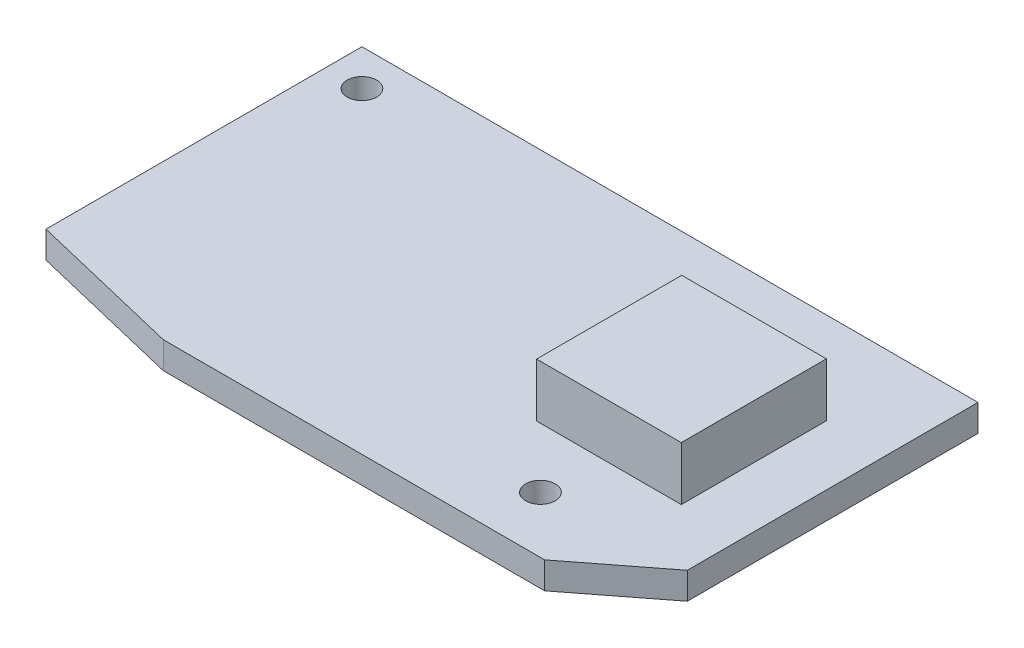
SolidWorks part; units mm, degrees
ref_plane "前视基准面" through (0, 0, 0) normal (0, 0, 1) x (1, 0, 0)
ref_plane "上视基准面" through (0, 0, 0) normal (0, 1, 0) x (1, 0, 0)
ref_plane "右视基准面" through (0, 0, 0) normal (1, 0, 0) x (0, 0, -1)
other "Configuration Table"
sketch "草图1" plane through (0, 0, 0) normal (0, 1, 0) x (1, 0, 0)
  line L0 (0, 0) -> (45.9, 0)
  line L1 (45.9, 0) -> (45.9, -21.6587)
  line L2 (39.913, -26.3) -> (11.5043, -26.3)
  line L3 (0, -23.537) -> (0, 0)
  line L4 (11.5043, -26.3) -> (0, -23.537)
  line L5 (39.913, -26.3) -> (45.9, -21.6587)
  dimension "D1" = 45.9
  dimension "D3" = 26.3
extrude "凸台-拉伸2" add sketch "草图1" along normal blind 2
sketch "草图2" plane through (0, 2, 0) normal (0, 1, 0) x (1, 0, 0)
  line L1 (30.6584, -6.8329) -> (41.4375, -6.8329)
  line L2 (30.6584, -6.8329) -> (30.6584, -17.6439)
  line L3 (30.6584, -17.6439) -> (41.4375, -17.6439)
  line L4 (41.4375, -6.8329) -> (41.4375, -17.6439)
extrude "凸台-拉伸3" add sketch "草图2" along normal blind 4
sketch "草图3" plane through (0, 2, 0) normal (0, 1, 0) x (1, 0, 0)
  line L0 (11.5043, -26.3) -> (39.913, -26.3) construction
  line L1 (0, 0) -> (0, -23.537) construction
  line L2 (45.9, 0) -> (0, 0) construction
  circle A0 centre (2.7, -2.7) radius 1.1
  circle A1 centre (35.4, -22.1) radius 1.1
  dimension "D1" = 2.2
  dimension "D2" = 2.2
  dimension "D3" = 4.2
  dimension "D4" = 35.4
  dimension "D5" = 2.7
  dimension "D6" = 2.7
extrude "切除-拉伸1" cut sketch "草图3" against normal blind 4
equation "\"D3@草图3\"=3.4+0.8"
equation "\"D4@草图3\"=34.6+0.8"
equation "\"D5@草图3\"=1.9+0.8"
equation "\"D6@草图3\"=\"D5@草图3\""
